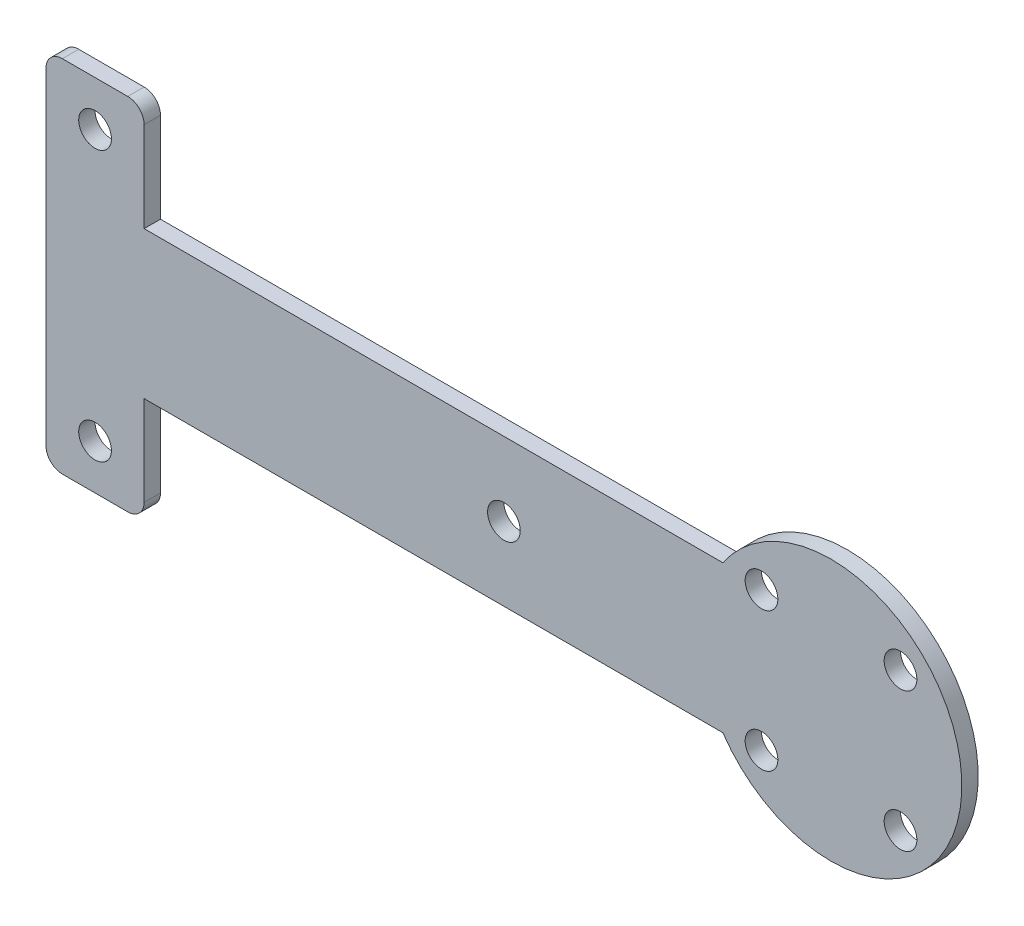
SolidWorks part; units mm, degrees
ref_plane "前视基准面" through (0, 0, 0) normal (0, 0, 1) x (1, 0, 0)
ref_plane "上视基准面" through (0, 0, 0) normal (0, 1, 0) x (1, 0, 0)
ref_plane "右视基准面" through (0, 0, 0) normal (1, 0, 0) x (0, 0, -1)
sketch "草图1" plane through (0, 0, 0) normal (0, 0, 1) x (1, 0, 0)
  line L0 (41.2764, 0.1457) -> (41.2764, 6.1457)
  line L3 (-42.7236, 9.1457) -> (-42.7236, 22.1457)
  line L4 (-42.7236, 22.1457) -> (-54.7236, 22.1457)
  line L5 (-54.7236, 22.1457) -> (-54.7236, -21.8543)
  line L6 (-54.7236, -21.8543) -> (-42.7236, -21.8543)
  line L7 (-42.7236, -21.8543) -> (-42.7236, -8.8543)
  line L8 (41.2764, 0.1457) -> (49.7764, 0.1457) construction
  line L9 (49.7764, 0.1457) -> (49.7764, -8.3543) construction
  line L10 (-42.7236, 9.1457) -> (28.0477, 9.1457)
  line L11 (-42.7236, -8.8543) -> (28.0477, -8.8543)
  circle A1 centre (1.2764, 0.1457) radius 2
  circle A2 centre (-48.7236, 16.6457) radius 2
  circle A3 centre (-48.7236, -16.3543) radius 2
  circle A10 centre (49.7764, -8.3543) radius 2
  circle A11 centre (32.7764, -8.3543) radius 2
  circle A12 centre (32.7764, 8.6457) radius 2
  circle A13 centre (49.7764, 8.6457) radius 2
  circle A14 centre (41.2764, 0.1457) radius 16 construction
  arc A15 (28.0477, 9.1457) -> (28.0477, -8.8543) centre (41.2764, 0.1457) cw
  dimension "D1" = 4
  dimension "D5" = 33
  dimension "D4" = 4
  dimension "D2" = 6
  dimension "D6" = 13
  dimension "D7" = 12
  dimension "D8" = 90
  dimension "D9" = 6
extrude "凸台-拉伸1" add sketch "草图1" along normal blind 2
fillet "圆角1" radius 2 4 edges at (-42.7236, 22.1457, 1) (-54.7236, 22.1457, 1) (-42.7236, -21.8543, 1) (-54.7236, -21.8543, 1)
